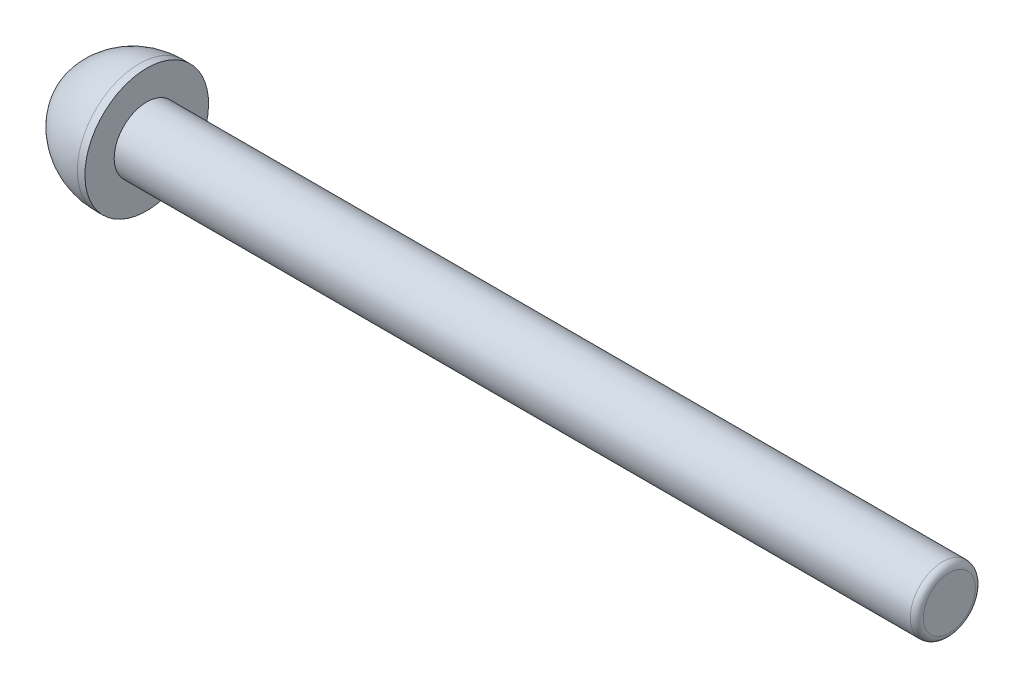
SolidWorks part; units mm, degrees
ref_plane "Plan de face" through (0, 0, 0) normal (0, 0, 1) x (1, 0, 0)
ref_plane "Plan de dessus" through (0, 0, 0) normal (0, 1, 0) x (1, 0, 0)
ref_plane "Plan de droite" through (0, 0, 0) normal (1, 0, 0) x (0, 0, -1)
sketch "Esquisse1" plane through (0, 0, 0) normal (0, 0, 1) x (1, 0, 0)
  line L0 (40.1649, 0) -> (0, 0)
  line L1 (0, 0) -> (0, 1.43)
  line L2 (2.8149, 2.85) -> (3.1649, 2.85)
  line L3 (3.1649, 2.85) -> (3.1649, 1.5)
  line L4 (3.1649, 1.5) -> (40.1649, 1.5)
  line L5 (40.1649, 1.5) -> (40.1649, 0)
  arc A0 (0, 1.43) -> (2.8149, 2.85) centre (2.8149, -0.65) cw
  dimension "D5" = 3.5
  dimension "D1" = 37
  dimension "D2" = 1.5
  dimension "D3" = 2.85
  dimension "D4" = 0.35
  dimension "D6" = 1.43
revolve "Révolution1" add sketch "Esquisse1" angle 360 about L0
fillet "Congé1" radius 0.3 1 edges at (40.1649, 1.5, 0)
sketch "Esquisse2" plane through (0, 0, 0) normal (-1, 0, 0) x (0, 0, 1)
  line L1 (0, 1.1547) -> (-1, 0.5774)
  line L2 (-1, 0.5774) -> (-1, -0.5774)
  line L3 (-1, -0.5774) -> (0, -1.1547)
  line L4 (0, -1.1547) -> (1, -0.5774)
  line L5 (1, -0.5774) -> (1, 0.5774)
  line L6 (1, 0.5774) -> (0, 1.1547)
  circle A0 centre (0, 0) radius 1 construction
  dimension "D1" = 2
extrude "Enlèv. mat.-Extru.1" cut sketch "Esquisse2" against normal blind 1
